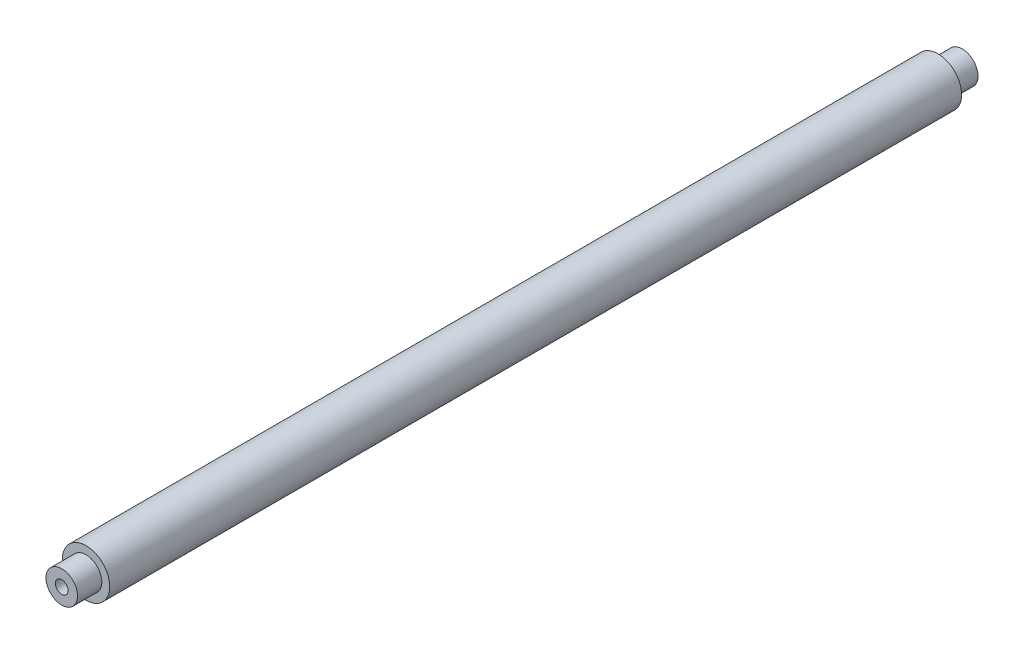
SolidWorks part; units mm, degrees
ref_plane "Front" through (0, 0, 0) normal (0, 0, 1) x (1, 0, 0)
ref_plane "Top" through (0, 0, 0) normal (0, 1, 0) x (1, 0, 0)
ref_plane "Right" through (0, 0, 0) normal (1, 0, 0) x (0, 0, -1)
sketch "Sketch1" plane through (0, 0, 0) normal (0, 0, 1) x (1, 0, 0)
  circle A0 centre (0, 0) radius 9.525
  dimension "D1" = 19.05
extrude "Boss-Extrude1" add sketch "Sketch1" along normal blind 342.9
sketch "Sketch2" plane through (0, 0, 342.9) normal (0, 0, 1) x (1, 0, 0)
  circle A0 centre (0, 0) radius 6.35
  dimension "D1" = 12.7
extrude "Boss-Extrude2" add sketch "Sketch2" along normal blind 9.779
hole_wizard "1/4-20 Tapped Hole1" positions "Sketch3" profile "Sketch4" tap size "1/4-20" standard "ANSI Inch"
sketch "Sketch3" plane through (0, 0, 352.679) normal (0, 0, 1) x (1, 0, 0)
  point P0 (0, 0)
sketch "Sketch4" plane through (0, 0, 352.679) normal (1, 0, 0) x (0, -1, 0)
  line L0 (0, 0) -> (0, 26.9338)
  line L1 (0, 26.9338) -> (2.5527, 25.4)
  line L2 (2.5527, 25.4) -> (2.5527, 0)
  line L5 (2.5527, 0) -> (0, 0)
  line L10 (0, 26.9338) -> (-2.5527, 25.4) construction
  line L11 (0, -6.35) -> (0, 107.95) construction
  dimension "Tap Drill Dia." = 5.1054
  dimension "Tap Drill Depth" = 25.4
  dimension "Drill Angle" = 118
sketch "Sketch5" plane through (0, 0, 0) normal (0, 0, -1) x (-1, 0, 0)
  circle A0 centre (0, 0) radius 6.35
  dimension "D1" = 12.7
extrude "Boss-Extrude3" add sketch "Sketch5" along normal blind 9.779
hole_wizard "1/4-20 Tapped Hole2" positions "Sketch6" profile "Sketch7" tap size "1/4-20" standard "ANSI Inch"
sketch "Sketch6" plane through (0, 0, -9.779) normal (0, 0, -1) x (-1, 0, 0)
  point P0 (0, 0)
sketch "Sketch7" plane through (0, 0, -9.779) normal (1, 0, 0) x (0, 1, 0)
  line L0 (0, 0) -> (0, 26.9338)
  line L1 (0, 26.9338) -> (2.5527, 25.4)
  line L2 (2.5527, 25.4) -> (2.5527, 0)
  line L5 (2.5527, 0) -> (0, 0)
  line L10 (0, 26.9338) -> (-2.5527, 25.4) construction
  line L11 (0, -6.35) -> (0, 107.95) construction
  dimension "Tap Drill Dia." = 5.1054
  dimension "Tap Drill Depth" = 25.4
  dimension "Drill Angle" = 118
